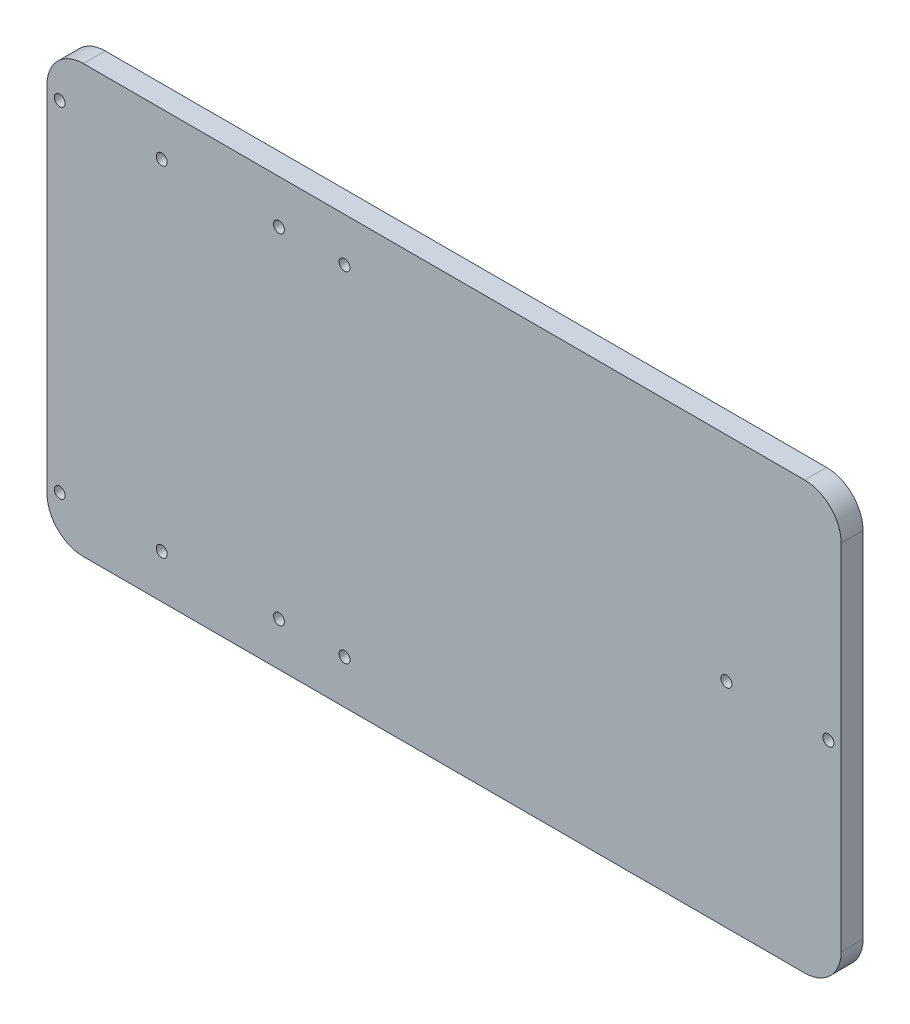
SolidWorks part; units mm, degrees
ref_plane "Front Plane" through (0, 0, 0) normal (0, 0, 1) x (1, 0, 0)
ref_plane "Top Plane" through (0, 0, 0) normal (0, 1, 0) x (1, 0, 0)
ref_plane "Right Plane" through (0, 0, 0) normal (1, 0, 0) x (0, 0, -1)
sketch "Sketch1" plane through (0, 0, 0) normal (0, 0, 1) x (1, 0, 0)
  line L0 (-242.1092, 256.3436) -> (-242.1092, 139.1436) construction
  line L1 (-59.1092, 256.3436) -> (-59.1092, 139.1436) construction
  line L2 (-242.1092, 139.1436) -> (-59.1092, 139.1436) construction
  line L3 (-150.6092, 256.3436) -> (-150.6092, 306.7436) construction
  line L4 (-238.1092, 139.1436) -> (-246.1092, 139.1436) construction
  line L5 (-242.1092, 256.3436) -> (-59.1092, 256.3436) construction
  line L6 (-238.1092, 139.1436) -> (-238.1092, 256.3436) construction
  line L7 (-238.1092, 256.3436) -> (-246.1092, 256.3436) construction
  line L8 (-246.1092, 139.1436) -> (-246.1092, 256.3436) construction
  line L9 (-238.1092, 139.1436) -> (-246.1092, 256.3436) construction
  line L10 (-238.1092, 256.3436) -> (-246.1092, 139.1436) construction
  line L11 (-55.1092, 139.1436) -> (-63.1092, 139.1436) construction
  line L12 (-55.1092, 139.1436) -> (-55.1092, 256.3436) construction
  line L13 (-55.1092, 256.3436) -> (-63.1092, 256.3436) construction
  line L14 (-63.1092, 139.1436) -> (-63.1092, 256.3436) construction
  line L15 (-55.1092, 139.1436) -> (-63.1092, 256.3436) construction
  line L16 (-55.1092, 256.3436) -> (-63.1092, 139.1436) construction
  line L17 (-231.6092, 232.3436) -> (-252.6092, 232.3436)
  line L18 (-231.6092, 232.3436) -> (-231.6092, 256.3436)
  line L19 (-231.6092, 256.3436) -> (-252.6092, 256.3436)
  line L20 (-252.6092, 232.3436) -> (-252.6092, 256.3436)
  line L21 (-231.6092, 232.3436) -> (-252.6092, 256.3436) construction
  line L22 (-231.6092, 256.3436) -> (-252.6092, 232.3436) construction
  line L23 (-252.6092, 163.1436) -> (-231.6092, 163.1436)
  line L24 (-252.6092, 163.1436) -> (-252.6092, 139.1436)
  line L25 (-252.6092, 139.1436) -> (-231.6092, 139.1436)
  line L26 (-231.6092, 163.1436) -> (-231.6092, 139.1436)
  line L27 (-252.6092, 163.1436) -> (-231.6092, 139.1436) construction
  line L28 (-252.6092, 139.1436) -> (-231.6092, 163.1436) construction
  line L29 (-48.6092, 185.7436) -> (-69.6092, 185.7436) construction
  line L30 (-48.6092, 185.7436) -> (-48.6092, 209.7436) construction
  line L31 (-48.6092, 209.7436) -> (-69.6092, 209.7436) construction
  line L32 (-69.6092, 185.7436) -> (-69.6092, 209.7436) construction
  line L33 (-48.6092, 185.7436) -> (-69.6092, 209.7436) construction
  line L34 (-48.6092, 209.7436) -> (-69.6092, 185.7436) construction
  line L35 (-150.6092, 306.7436) -> (-259.6092, 306.7436) construction
  line L37 (-259.6092, 256.3436) -> (-41.6092, 256.3436)
  line L38 (-259.6092, 306.7436) -> (-41.6092, 306.7436)
  line L39 (-259.6092, 306.7436) -> (-259.6092, 88.7436)
  line L40 (-259.6092, 88.7436) -> (-41.6092, 88.7436)
  line L41 (-41.6092, 306.7436) -> (-41.6092, 88.7436)
  line L42 (-259.6092, 256.3436) -> (-259.6092, 139.1436)
  line L43 (-259.6092, 139.1436) -> (-41.6092, 139.1436)
  line L44 (-41.6092, 256.3436) -> (-41.6092, 139.1436)
  circle A0 centre (-269.6092, 244.3436) radius 2.5
  circle A1 centre (-31.6092, 197.7436) radius 2.5
  circle A3 centre (-269.6092, 151.1436) radius 2.5
  circle A6 centre (-256.1092, 244.3436) radius 1.5
  circle A7 centre (-256.1092, 151.1436) radius 1.5
  circle A8 centre (-45.1092, 197.7436) radius 1.5
  circle A9 centre (-73.1092, 197.7436) radius 1.5
  circle A10 centre (-228.1092, 244.3436) radius 1.5
  circle A11 centre (-228.1092, 151.1436) radius 1.5
  point P0 (-242.1092, 197.7436)
  point P9 (-59.1092, 197.7436)
  point P14 (-242.1092, 244.3436)
  point P19 (-242.1092, 151.1436)
  point P24 (-59.1092, 197.7436)
  point P34 (-150.6092, 197.7436)
  dimension "D11" = 5
  dimension "D12" = 10
  dimension "D15" = 3
  dimension "D20" = 5
  dimension "D21" = 10
  dimension "D22" = 5
  dimension "D23" = 3.5
  dimension "D24" = 3.5
  dimension "D1" = 183
  dimension "D2" = 8
  dimension "D3" = 8
  dimension "D4" = 21
  dimension "D5" = 24
  dimension "D6" = 117.2
  dimension "D7" = 21
  dimension "D8" = 24
  dimension "D9" = 21
  dimension "D10" = 24
  dimension "D16" = 109
  dimension "D17" = 109
  dimension "D18" = 218
  dimension "D19" = 218
extrude "Boss-Extrude1" add sketch "Sketch1" along normal blind 6 contours A6 | A10 | A11 | A8 | A9 | L37 L44 L43 L42 | A7
sketch "Sketch2" plane through (0, 0, 6) normal (0, 0, 1) x (1, 0, 0)
  line L0 (-259.6092, 256.3436) -> (-41.6092, 256.3436) construction
  line L1 (-259.6092, 256.3436) -> (-41.6092, 256.3436)
  line L2 (-186.9425, 273.3122) -> (-186.9425, 128.0805) construction
  line L3 (-259.6092, 256.3436) -> (-259.6092, 139.1436) construction
  line L4 (-256.1092, 244.3436) -> (-152.9234, 244.3436) construction
  line L5 (-256.1092, 151.1436) -> (-151.5972, 151.1436) construction
  circle A1 centre (-195.9425, 151.1436) radius 1.5
  circle A2 centre (-177.9425, 151.1436) radius 1.5
  circle A3 centre (-195.9425, 244.3436) radius 1.5
  circle A4 centre (-177.9425, 244.3436) radius 1.5
  dimension "D2" = 9
  dimension "D3" = 3
  dimension "D4" = 9
  dimension "D5" = 9
  dimension "D6" = 9
  dimension "D1" = 72.6667
extrude "Cut-Extrude1" cut sketch "Sketch2" against normal blind 6 contours A1 | A2 | A3 | A4
fillet "Fillet1" radius 10 4 edges at (-41.6092, 139.1436, 3) (-41.6092, 256.3436, 3) (-259.6092, 139.1436, 3) (-259.6092, 256.3436, 3)
